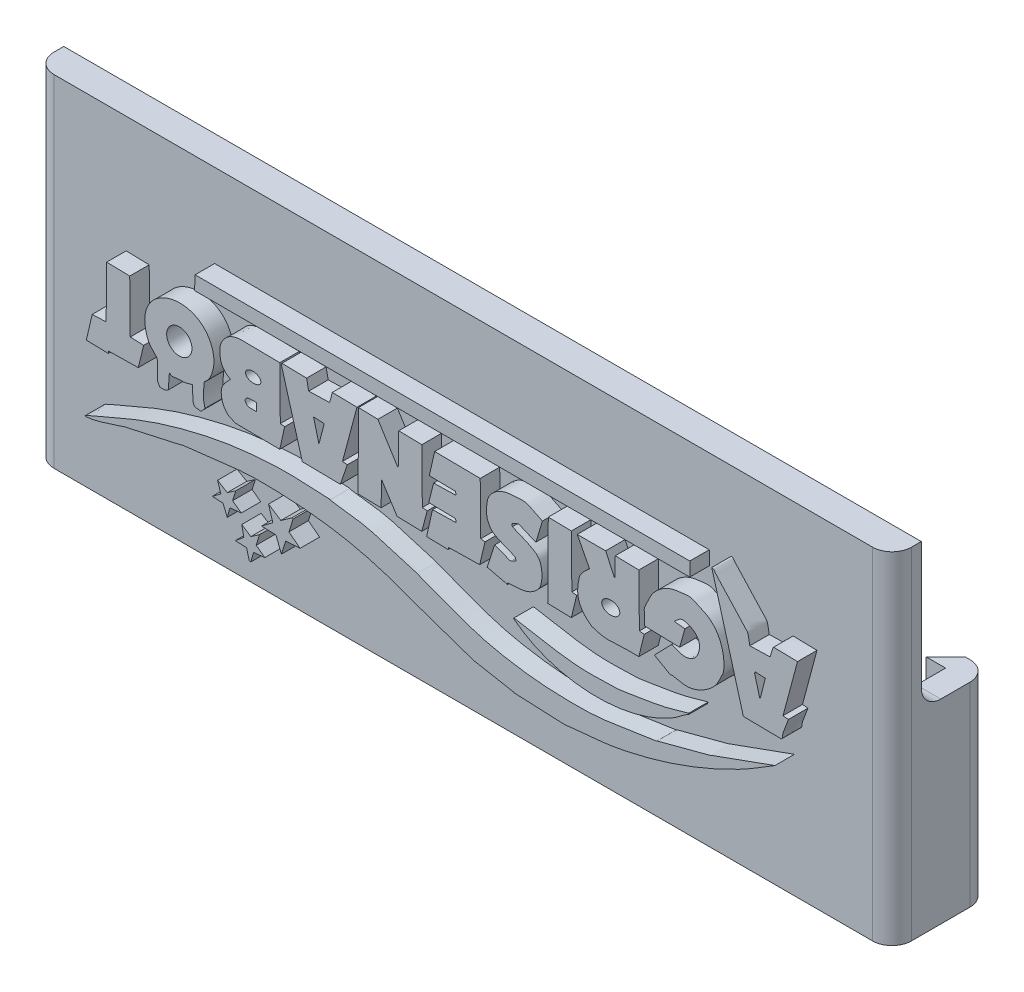
SolidWorks part; units mm, degrees
ref_plane "Front Plane" through (0, 0, 0) normal (0, 0, 1) x (1, 0, 0)
ref_plane "Top Plane" through (0, 0, 0) normal (0, 1, 0) x (1, 0, 0)
ref_plane "Right Plane" through (0, 0, 0) normal (1, 0, 0) x (0, 0, -1)
sketch "Sketch1" plane through (0, 0, 0) normal (0, 1, 0) x (1, 0, 0)
  line L0 (-41.5, 8.5) -> (-39.5, 6.5)
  line L1 (-44, 1.5) -> (44, 1.5)
  line L2 (-44, 1.5) -> (-44, 0.5)
  line L3 (-42, -1.5) -> (42, -1.5)
  line L4 (44, 1.5) -> (44, 0.5)
  line L5 (-44, 1.5) -> (44, -1.5) construction
  line L6 (-44, -1.5) -> (44, 1.5) construction
  line L7 (-44, -1.5) -> (-41.5, -1.5)
  line L8 (-44, -1.5) -> (-44, 6.5)
  line L9 (-42, 8.5) -> (-41.5, 8.5)
  line L10 (-41.5, -1.5) -> (-41.5, 8.5)
  line L11 (-39.5, 6.5) -> (-41.5, 6.5)
  line L12 (-41.5, 6.5) -> (-41.5, 8.5)
  line L13 (0, 10.3382) -> (0, -6.5943) construction
  line L14 (44, -1.5) -> (44, 6.5)
  line L15 (41.5, -1.5) -> (41.5, 8.5)
  line L16 (41.5, 6.5) -> (41.5, 8.5)
  line L17 (39.5, 6.5) -> (41.5, 6.5)
  line L18 (42, 8.5) -> (41.5, 8.5)
  line L19 (41.5, 8.5) -> (39.5, 6.5)
  arc A0 (44, 6.5) -> (42, 8.5) centre (42, 6.5) ccw
  arc A1 (42, -1.5) -> (44, 0.5) centre (42, 0.5) ccw
  arc A2 (-44, 0.5) -> (-42, -1.5) centre (-42, 0.5) ccw
  arc A3 (-44, 6.5) -> (-42, 8.5) centre (-42, 6.5) cw
  point P0 (0, 0)
  point P20 (44, 8.5)
  point P29 (-44, 8.5)
  dimension "D6" = 2
  dimension "D1" = 7
  dimension "35" = 3
  dimension "D2" = 88
  dimension "D3" = 2.5
  dimension "D4" = 2
  dimension "D5" = 2
extrude "Boss-Extrude2" add sketch "Sketch1" along normal blind 35 contours L3 L15 L1 L10 | L14 A0 L18 L15 L1 | L3 A1 L4 L1 L15 | L11 L0 L10 | A3 L8 L1 L10 L9 | L2 A2 L3 L10 L1 | L19 L17 L16
sketch "Sketch2" plane through (0, 35, 0) normal (0, 1, 0) x (1, 0, 0)
  line L1 (-47.8028, 11.6692) -> (46.9509, 11.6692)
  line L2 (-47.8028, 11.6692) -> (-47.8028, 1.5)
  line L3 (-47.8028, 1.5) -> (46.9509, 1.5)
  line L4 (46.9509, 11.6692) -> (46.9509, 1.5)
extrude "Cut-Extrude1" cut sketch "Sketch2" against normal blind 15
fillet "Fillet1" radius 2 2 edges at (-42.75, 20, -1.5) (42.75, 20, -1.5)
sketch "Sketch8" plane through (0, 0, 1.5) normal (0, 0, 1) x (1, 0, 0)
  line L0 (438.3015, -119.9057) -> (-448.3652, -119.9057) construction
  line L1 (-34.4318, 15.0029) -> (-36.6868, 15.0579)
  line L2 (-36.6868, 15.0579) -> (-36.0818, 17.6429)
  line L3 (-36.0818, 17.6429) -> (-34.6518, 17.6979)
  line L4 (-34.6518, 17.6979) -> (-34.5968, 23.0329)
  line L5 (-34.5968, 23.0329) -> (-32.2318, 22.9779)
  line L6 (-32.2318, 22.9779) -> (-32.1768, 17.5879)
  line L7 (-32.1768, 17.5879) -> (-30.8018, 17.5329)
  line L8 (-30.8018, 17.5329) -> (-31.3518, 15.2779)
  line L9 (-31.3518, 15.2779) -> (-34.4318, 15.2229)
  line L10 (-34.4318, 15.2229) -> (-34.4318, 15.0029)
  line L11 (-28.1618, 16.4329) -> (-28.2718, 14.8379)
  line L12 (-16.8318, 22.9779) -> (-16.7768, 17.5879)
  line L13 (-16.7768, 17.5879) -> (-16.3368, 17.5329)
  line L14 (-16.3368, 17.5329) -> (-16.8318, 15.2779)
  line L15 (-19.1968, 18.2479) -> (-19.1968, 17.4229)
  line L16 (25.2432, 24.9579) -> (-25.5768, 25.0129)
  line L17 (-25.5768, 25.0129) -> (-25.5218, 26.4429)
  line L18 (-25.5218, 26.4429) -> (25.2432, 26.3879)
  line L19 (25.2432, 26.3879) -> (25.2432, 24.9579)
  line L20 (-10.6168, 15.2779) -> (-14.5218, 15.3329)
  line L21 (-14.5218, 15.3329) -> (-16.6668, 22.8679)
  line L22 (-16.6668, 22.8679) -> (-16.6118, 23.0329)
  line L23 (-16.6118, 23.0329) -> (-14.0818, 22.9779)
  line L24 (-14.0818, 22.9779) -> (-13.8618, 21.9329)
  line L25 (-13.8618, 21.9329) -> (-11.7168, 21.9879)
  line L26 (-11.7168, 21.9879) -> (-11.4418, 23.0329)
  line L27 (-11.4418, 23.0329) -> (-8.9118, 22.9779)
  line L28 (-8.9118, 22.9779) -> (-10.3968, 17.4229)
  line L29 (-10.3968, 17.4229) -> (-9.9018, 17.3679)
  line L30 (-9.9018, 17.3679) -> (-10.6168, 15.2779)
  line L31 (-12.8168, 17.7529) -> (-13.3668, 19.8979)
  line L32 (-13.3668, 19.8979) -> (-12.2668, 19.8429)
  line L33 (-12.2668, 19.8429) -> (-12.8168, 17.7529)
  line L34 (-2.2568, 15.2779) -> (-4.7868, 15.3329)
  line L35 (-4.7868, 15.3329) -> (-6.3818, 17.8079)
  line L36 (-6.3818, 17.8079) -> (-6.4368, 15.2779)
  line L37 (-6.4368, 15.2779) -> (-8.8018, 15.3329)
  line L38 (-8.8018, 15.3329) -> (-8.7468, 23.0329)
  line L39 (-8.7468, 23.0329) -> (-6.7668, 22.9779)
  line L40 (-6.7668, 22.9779) -> (-4.6768, 19.6779)
  line L41 (-4.6768, 19.6779) -> (-4.6218, 23.0329)
  line L42 (-4.6218, 23.0329) -> (-2.2568, 22.9779)
  line L43 (-2.2568, 22.9779) -> (-2.2018, 17.4229)
  line L44 (-2.2018, 17.4229) -> (-1.7068, 17.3679)
  line L45 (-1.7068, 17.3679) -> (-2.2568, 15.2779)
  line L46 (0.4382, 15.0029) -> (-1.7618, 15.0579)
  line L47 (-1.7618, 15.0579) -> (-1.1568, 17.7529)
  line L48 (-1.1568, 17.7529) -> (1.2632, 17.8079)
  line L49 (1.2632, 17.8079) -> (1.2082, 18.1379)
  line L50 (1.2082, 18.1379) -> (-1.5418, 18.1929)
  line L51 (-1.5418, 18.1929) -> (-1.0468, 20.1729)
  line L52 (-1.0468, 20.1729) -> (1.2632, 20.2279)
  line L53 (1.2632, 20.2279) -> (1.2082, 20.5579)
  line L54 (1.2082, 20.5579) -> (-1.4868, 20.6129)
  line L55 (-1.4868, 20.6129) -> (-0.9368, 23.0329)
  line L56 (-0.9368, 23.0329) -> (3.7382, 22.9779)
  line L57 (3.7382, 22.9779) -> (3.7932, 17.6429)
  line L58 (3.7932, 17.6429) -> (4.2332, 17.5879)
  line L59 (4.2332, 17.5879) -> (3.6832, 15.2779)
  line L60 (3.6832, 15.2779) -> (0.4932, 15.2229)
  line L61 (0.4932, 15.2229) -> (0.4382, 15.0029)
  line L62 (6.5432, 14.9479) -> (4.4532, 15.4429)
  line L63 (4.4532, 15.4429) -> (5.2232, 17.8079)
  line L64 (10.1182, 22.3729) -> (9.4582, 20.1729)
  line L65 (6.9832, 20.6129) -> (7.0382, 20.3379)
  line L66 (6.5432, 15.1129) -> (6.5432, 14.9479)
  line L67 (13.0882, 15.2779) -> (10.6682, 15.3329)
  line L68 (10.6682, 15.3329) -> (10.7232, 23.0329)
  line L69 (10.7232, 23.0329) -> (13.0882, 22.9779)
  line L70 (13.0882, 22.9779) -> (13.1432, 17.5879)
  line L71 (13.1432, 17.5879) -> (13.6382, 17.5329)
  line L72 (13.6382, 17.5329) -> (13.0882, 15.2779)
  line L73 (14.9582, 20.5579) -> (13.6932, 22.9779)
  line L74 (13.6932, 22.9779) -> (16.6082, 22.9779)
  line L75 (16.6082, 22.9779) -> (17.5432, 20.9979)
  line L76 (17.5432, 20.9979) -> (17.5982, 23.0329)
  line L77 (17.5982, 23.0329) -> (20.0182, 22.9779)
  line L78 (20.0182, 22.9779) -> (20.0732, 17.5879)
  line L79 (20.0732, 17.5879) -> (20.5682, 17.5329)
  line L80 (20.5682, 17.5329) -> (20.0182, 15.2779)
  line L81 (23.2632, 15.2779) -> (21.6132, 16.2129)
  line L82 (21.6132, 16.2129) -> (23.3732, 18.0279)
  line L83 (23.6482, 20.2279) -> (24.7482, 20.1179)
  line L84 (24.7482, 20.1179) -> (24.1982, 18.1929)
  line L85 (24.1982, 18.1929) -> (20.6232, 18.3029)
  line L86 (30.7432, 15.3329) -> (27.4982, 26.9379)
  line L87 (31.4032, 21.9329) -> (33.4932, 21.9879)
  line L88 (36.2982, 22.9779) -> (34.8132, 17.4229)
  line L89 (34.8132, 17.4229) -> (35.3632, 17.3679)
  line L90 (32.4482, 17.6979) -> (31.8982, 19.7329)
  line L91 (31.8982, 19.7329) -> (31.9532, 19.8979)
  line L92 (31.9532, 19.8979) -> (32.9982, 19.8429)
  line L93 (32.9982, 19.8429) -> (32.4482, 17.6979)
  line L94 (7.1482, 12.2529) -> (7.2032, 12.3079)
  line L95 (25.1332, 12.8029) -> (25.0782, 12.6379)
  line L96 (-16.6668, 6.0379) -> (-17.2168, 7.4679)
  line L97 (-17.2168, 7.4679) -> (-18.7018, 7.5229)
  line L98 (-18.7018, 7.5229) -> (-17.5468, 8.4029)
  line L99 (-17.5468, 8.4029) -> (-17.9868, 9.8329)
  line L100 (-17.9868, 9.8329) -> (-16.7218, 9.0079)
  line L101 (-16.7218, 9.0079) -> (-15.5668, 9.8329)
  line L102 (-15.5668, 9.8329) -> (-15.4568, 9.7779)
  line L103 (-15.4568, 9.7779) -> (-15.8968, 8.4029)
  line L104 (-15.8968, 8.4029) -> (-14.7418, 7.5229)
  line L105 (-14.7418, 7.5229) -> (-16.2268, 7.4129)
  line L106 (-16.2268, 7.4129) -> (-16.6668, 6.0379)
  line L107 (-19.8018, 3.7829) -> (-19.9668, 3.8379)
  line L108 (-19.9668, 3.8379) -> (-20.2418, 4.8279)
  line L109 (-20.2418, 4.8279) -> (-21.3968, 4.8829)
  line L110 (-21.3968, 4.8829) -> (-20.5168, 5.5979)
  line L111 (-20.5168, 5.5979) -> (-20.7368, 6.6429)
  line L112 (-20.7368, 6.6429) -> (-19.8018, 6.0379)
  line L113 (-19.8018, 6.0379) -> (-18.9218, 6.6429)
  line L114 (-18.9218, 6.6429) -> (-19.2518, 5.5429)
  line L115 (-19.2518, 5.5429) -> (-18.3718, 4.8829)
  line L116 (-18.3718, 4.8829) -> (-19.5268, 4.7729)
  line L117 (-19.5268, 4.7729) -> (-19.8018, 3.7829)
  line L118 (-22.2218, 6.5329) -> (-22.6618, 7.5779)
  line L119 (-22.6618, 7.5779) -> (-23.7618, 7.6329)
  line L120 (-23.7618, 7.6329) -> (-22.8818, 8.2929)
  line L121 (-22.8818, 8.2929) -> (-23.2118, 9.3379)
  line L122 (-23.2118, 9.3379) -> (-22.2218, 8.7329)
  line L123 (-22.2218, 8.7329) -> (-21.3418, 9.3379)
  line L124 (-21.3418, 9.3379) -> (-21.6718, 8.2929)
  line L125 (-21.6718, 8.2929) -> (-20.7918, 7.6329)
  line L126 (-20.7918, 7.6329) -> (-21.9468, 7.5229)
  line L127 (-21.9468, 7.5229) -> (-22.2218, 6.5329)
  circle A0 centre (-27.1429, 19.7155) radius 1.2982
  ellipse E0 centre (-19.5569, 20.3182) end of major axis (-18.7736, 20.2759) minor radius 0.5234
  ellipse E1 centre (17.1363, 18.1867) end of major axis (16.2095, 18.1687) minor radius 0.6718
  spline S0 degree 3 poles (-24.9168, 14.6179) (-25.4901, 14.67) (-25.7016, 14.621) (-25.7418, 15.2229) (-25.771, 15.6623) (-25.7784, 16.1029) (-25.7968, 16.5429) knots 0 0 0 0 1 1 1 2 2 2 2
  spline S1 degree 3 poles (-25.7968, 16.5429) (-26.1436, 16.4628) (-26.4858, 16.3229) (-26.8418, 16.3229) (-28.0765, 16.3229) (-27.8118, 16.0829) (-28.1618, 16.4329) knots 0 0 0 0 1 1 1 2 2 2 2
  spline S2 degree 3 poles (-28.2718, 14.8379) (-28.5837, 14.6039) (-28.7716, 14.6095) (-29.1518, 14.6729) knots 0 0 0 0 1 1 1 1
  spline S3 degree 3 poles (-29.1518, 14.6729) (-29.2251, 14.8195) (-29.3532, 14.9499) (-29.3718, 15.1129) (-29.4463, 15.7689) (-29.2732, 16.4507) (-29.4268, 17.0929) (-29.4295, 17.1045) (-30.1953, 17.8779) (-30.3068, 18.1379) (-32.3876, 22.9932) (-25.4068, 25.0769) (-23.8168, 20.9429) (-23.4299, 19.937) (-23.5638, 19.0023) (-23.9818, 18.0829) (-24.0516, 17.9293) (-24.1966, 17.7772) (-24.3118, 17.6429) (-24.4049, 17.5342) (-24.5697, 17.455) (-24.5868, 17.3129) (-24.9077, 14.6386) (-24.0663, 15.4683) (-24.9168, 14.6179) knots 0 0 0 0 1 1 1 2 2 2 3 3 3 4 4 4 5 5 5 6 6 6 7 7 7 8 8 8 8
  spline S4 degree 3 poles (-16.8318, 15.2779) (-18.3718, 15.2962) (-19.9121, 15.2966) (-21.4518, 15.3329) (-21.4777, 15.3335) (-21.4836, 15.3763) (-21.5068, 15.3879) (-21.7049, 15.4869) (-21.9322, 15.5332) (-22.1118, 15.6629) (-22.3277, 15.8188) (-22.6427, 16.2714) (-22.7168, 16.5429) (-23.0558, 17.7861) (-22.6753, 18.1793) (-21.8918, 18.9629) knots 0 0 0 0 1 1 1 2 2 2 3 3 3 4 4 4 5 5 5 5
  spline S5 degree 3 poles (-21.8918, 18.9629) (-22.3234, 19.1787) (-22.7663, 19.6328) (-22.8818, 20.1179) (-23.1294, 21.1581) (-22.9886, 21.9251) (-22.1668, 22.5929) (-21.8216, 22.8733) (-21.2162, 23.0278) (-20.7918, 23.0329) (-19.4717, 23.0486) (-18.1518, 22.9962) (-16.8318, 22.9779) knots 0 0 0 0 1 1 1 2 2 2 3 3 3 4 4 4 4
  spline S6 degree 3 poles (-19.1968, 17.4229) (-19.8531, 17.4615) (-20.2485, 17.2847) (-20.4068, 17.9179) knots 0 0 0 0 1 1 1 1
  spline S7 degree 3 poles (-20.4068, 17.9179) (-20.3151, 18.0095) (-20.2579, 18.1628) (-20.1318, 18.1929) (-19.828, 18.2652) (-19.5084, 18.2295) (-19.1968, 18.2479) knots 0 0 0 0 1 1 1 2 2 2 2
  spline S8 degree 3 poles (5.2232, 17.8079) (7.1398, 17.209) (6.4335, 16.983) (7.4232, 17.4779) knots 0 0 0 0 1 1 1 1
  spline S9 degree 3 poles (7.4232, 17.4779) (7.3682, 17.5879) (7.3655, 17.7477) (7.2582, 17.8079) (6.5926, 18.1813) (5.8052, 18.3225) (5.1682, 18.7429) (4.8622, 18.9448) (4.635, 19.2788) (4.5082, 19.6229) (4.3682, 20.0029) (4.3687, 20.4289) (4.3982, 20.8329) (4.4245, 21.1921) (4.4816, 21.5729) (4.6732, 21.8779) (4.901, 22.2402) (5.2329, 22.5523) (5.6082, 22.7579) (6.0257, 22.9865) (6.5083, 23.1112) (6.9832, 23.1429) (8.4205, 23.2387) (8.3659, 23.2491) (9.0182, 22.9229) (9.3849, 22.7395) (9.7516, 22.5562) (10.1182, 22.3729) knots 0 0 0 0 1 1 1 2 2 2 3 3 3 4 4 4 5 5 5 6 6 6 7 7 7 8 8 8 9 9 9 9
  spline S10 degree 3 poles (9.4582, 20.1729) (7.307, 20.89) (8.114, 21.1154) (6.9832, 20.6129) knots 0 0 0 0 1 1 1 1
  spline S11 degree 3 poles (7.0382, 20.3379) (7.8449, 19.9529) (8.7336, 19.7062) (9.4582, 19.1829) (9.7643, 18.9618) (9.9372, 18.5636) (10.0082, 18.1929) (10.1083, 17.6704) (10.0932, 17.1111) (9.9532, 16.5979) (9.8635, 16.2689) (9.611, 15.9903) (9.3482, 15.7729) (9.064, 15.5376) (8.7174, 15.3624) (8.3582, 15.2779) (7.7669, 15.1387) (7.1482, 15.1679) (6.5432, 15.1129) knots 0 0 0 0 1 1 1 2 2 2 3 3 3 4 4 4 5 5 5 6 6 6 6
  spline S12 degree 3 poles (20.0182, 15.2779) (16.6884, 15.3217) (16.9723, 14.9549) (15.1782, 15.5529) (15.1537, 15.5611) (15.1445, 15.593) (15.1232, 15.6079) (13.7565, 16.5646) (13.5092, 17.6767) (13.9132, 19.2929) (14.0399, 19.7995) (14.6254, 20.225) (14.9582, 20.5579) knots 0 0 0 0 1 1 1 2 2 2 3 3 3 4 4 4 4
  spline S13 degree 3 poles (20.6232, 18.3029) (20.6684, 19.794) (20.4083, 19.6012) (20.7332, 20.2279) (20.971, 20.6865) (21.1337, 21.193) (21.4482, 21.6029) (21.7486, 21.9942) (22.1252, 22.3391) (22.5482, 22.5929) (22.966, 22.8435) (23.4405, 23.0224) (23.9232, 23.0879) (25.0646, 23.2426) (25.2861, 23.2979) (25.9032, 22.9779) (26.3619, 22.7401) (26.872, 22.582) (27.2782, 22.2629) (27.6566, 21.9656) (27.9877, 21.588) (28.2132, 21.1629) (28.4742, 20.6711) (28.6415, 20.1205) (28.7082, 19.5679) (28.7695, 19.06) (28.8232, 18.3628) (28.5432, 17.8629) (28.3066, 17.4403) (28.1484, 16.9613) (27.8282, 16.5979) (27.4573, 16.1768) (26.9998, 15.8237) (26.5082, 15.5529) (26.0868, 15.3206) (25.6122, 15.1598) (25.1332, 15.1129) (24.6557, 15.066) (24.1783, 15.21) (23.7032, 15.2779) (23.5345, 15.302) (23.4409, 15.3667) (23.2632, 15.2779) knots 0 0 0 0 1 1 1 2 2 2 3 3 3 4 4 4 5 5 5 6 6 6 7 7 7 8 8 8 9 9 9 10 10 10 11 11 11 12 12 12 13 13 13 14 14 14 14
  spline S14 degree 3 poles (23.3732, 18.0279) (23.8316, 17.8995) (24.2724, 17.6542) (24.7482, 17.6429) (25.0787, 17.635) (25.4261, 17.7652) (25.6832, 17.9729) (25.9327, 18.1744) (26.1048, 18.4857) (26.1782, 18.7979) (26.2581, 19.1374) (26.2713, 19.527) (26.1232, 19.8429) (25.9746, 20.16) (25.6702, 20.4087) (25.3532, 20.5579) (24.3617, 21.0245) (24.2501, 20.7628) (23.6482, 20.2279) knots 0 0 0 0 1 1 1 2 2 2 3 3 3 4 4 4 5 5 5 6 6 6 6
  spline S15 degree 3 poles (35.3632, 17.3679) (35.1982, 16.8726) (34.9875, 16.362) (34.8132, 15.8829) (34.7399, 15.6812) (34.8078, 15.2779) (34.5932, 15.2779) (33.3098, 15.2779) (32.0266, 15.3145) (30.7432, 15.3329) knots 0 0 0 0 1 1 1 2 2 2 3 3 3 3
  spline S16 degree 3 poles (27.4982, 26.9379) (27.5532, 26.9195) (27.6196, 26.921) (27.6632, 26.8829) (27.771, 26.7886) (27.8431, 26.6599) (27.9382, 26.5529) (28.1365, 26.3298) (28.342, 26.1133) (28.5432, 25.8929) (29.1295, 25.2508) (29.7157, 24.6088) (30.3032, 23.9679) (30.5049, 23.7479) (30.71, 23.5309) (30.9082, 23.3079) (31.0034, 23.2008) (31.1347, 23.1126) (31.1832, 22.9779) (31.3038, 22.6429) (31.3299, 22.2812) (31.4032, 21.9329) knots 0 0 0 0 1 1 1 2 2 2 3 3 3 4 4 4 5 5 5 6 6 6 7 7 7 7
  spline S17 degree 3 poles (33.4932, 21.9879) (33.5849, 22.2995) (33.6559, 22.618) (33.7682, 22.9229) (33.7862, 22.9715) (33.8264, 23.0317) (33.8782, 23.0329) (34.6849, 23.0504) (35.4916, 22.9962) (36.2982, 22.9779) knots 0 0 0 0 1 1 1 2 2 2 3 3 3 3
  spline S18 degree 3 poles (25.0782, 12.6379) (24.7085, 12.5146) (24.0349, 11.9055) (23.7032, 11.7029) (22.865, 11.1906) (21.9954, 10.7768) (21.0632, 10.4379) (16.7063, 8.8535) (10.8699, 9.2756) (7.1482, 12.2529) knots 0 0 0 0 1 1 1 2 2 2 3 3 3 3
  spline S19 degree 3 poles (7.2032, 12.3079) (9.7209, 11.9205) (12.1507, 11.291) (14.7382, 11.2629) (15.7467, 11.2519) (16.7554, 11.2819) (17.7632, 11.3179) (18.134, 11.3311) (18.8971, 11.4702) (19.3032, 11.5379) (20.3986, 11.7204) (21.427, 11.8594) (22.4932, 12.0879) (23.2699, 12.2543) (24.3039, 12.5955) (25.1332, 12.8029) knots 0 0 0 0 1 1 1 2 2 2 3 3 3 4 4 4 5 5 5 5
  spline S20 degree 3 poles (-36.6868, 8.2379) (-37.2997, 8.1882) (-35.6001, 8.8164) (-35.0368, 9.0629) (-33.5458, 9.7152) (-32.0592, 10.3849) (-30.5268, 10.9329) (-29.0303, 11.4679) (-27.504, 11.9246) (-25.9618, 12.3079) (-24.4753, 12.6772) (-22.9691, 12.9789) (-21.4518, 13.1879) (-19.9028, 13.4012) (-18.34, 13.5375) (-16.7768, 13.5729) (-15.0896, 13.611) (-13.4028, 13.4796) (-11.7168, 13.4079) (-11.6758, 13.4061) (-11.6472, 13.3597) (-11.6068, 13.3529) (-10.0851, 13.0962) (-8.5183, 13.0314) (-7.0418, 12.5829) (-5.6321, 12.1546) (-4.2164, 11.7461) (-2.8068, 11.3179) (-2.7675, 11.306) (-2.7353, 11.2769) (-2.6968, 11.2629) (-0.6267, 10.5068) (1.405, 9.6332) (3.5182, 9.0079) (5.0077, 8.5671) (6.5454, 8.2912) (8.0832, 8.0729) (9.5213, 7.8687) (10.976, 7.7699) (12.4282, 7.7429) (13.9697, 7.7141) (15.5252, 7.7233) (17.0482, 7.9629) (18.6414, 8.2135) (20.2401, 8.4273) (21.8332, 8.6779) (21.8737, 8.6842) (21.9037, 8.7222) (21.9432, 8.7329) (23.7378, 9.2174) (25.5387, 9.6783) (27.3332, 10.1629) (27.3728, 10.1736) (27.4047, 10.2039) (27.4432, 10.2179) (29.6233, 11.0106) (31.8066, 11.7945) (33.9882, 12.5829) knots 20 20 20 20 21 21 21 22 22 22 23 23 23 24 24 24 25 25 25 26 26 26 27 27 27 28 28 28 29 29 29 30 30 30 31 31 31 32 32 32 33 33 33 34 34 34 35 35 35 36 36 36 37 37 37 38 38 38 39 39 39 39
  spline S21 degree 3 poles (33.9882, 12.5829) (32.8149, 11.8862) (31.6763, 11.1273) (30.4682, 10.4929) (29.1249, 9.7874) (27.7489, 9.1392) (26.3432, 8.5679) (24.9037, 7.9828) (23.4356, 7.4608) (21.9432, 7.0279) (20.4612, 6.5979) (18.9547, 6.241) (17.4332, 5.9829) (15.9242, 5.7268) (14.3897, 5.6551) (12.8682, 5.4879) (12.7213, 5.4717) (12.576, 5.4285) (12.4282, 5.4329) (10.7041, 5.4836) (8.9808, 5.5631) (7.2582, 5.6529) (7.2173, 5.655) (7.1885, 5.7001) (7.1482, 5.7079) (5.757, 5.9754) (4.3595, 6.2103) (2.9682, 6.4779) (2.928, 6.4856) (2.897, 6.5195) (2.8582, 6.5329) (1.2632, 7.0829) (-0.3351, 7.6232) (-1.9268, 8.1829) (-3.5567, 8.756) (-5.1623, 9.4067) (-6.8218, 9.8879) (-8.2656, 10.3065) (-9.7368, 10.6434) (-11.2218, 10.8779) (-12.8777, 11.1393) (-14.5518, 11.302) (-16.2268, 11.3729) (-18.0588, 11.4504) (-19.9075, 11.4927) (-21.7268, 11.2629) (-23.4301, 11.0477) (-25.1384, 10.873) (-26.8418, 10.6579) (-26.8824, 10.6527) (-26.9118, 10.612) (-26.9518, 10.6029) (-28.9296, 10.1534) (-30.9139, 9.7324) (-32.8918, 9.2829) (-32.9317, 9.2738) (-32.9622, 9.2387) (-33.0018, 9.2279) (-34.228, 8.8902) (-35.419, 8.3407) (-36.6868, 8.2379) knots 0 0 0 0 1 1 1 2 2 2 3 3 3 4 4 4 5 5 5 6 6 6 7 7 7 8 8 8 9 9 9 10 10 10 11 11 11 12 12 12 13 13 13 14 14 14 15 15 15 16 16 16 17 17 17 18 18 18 19 19 19 20 20 20 20
extrude "Boss-Extrude4" add sketch "Sketch8" along normal blind 2
